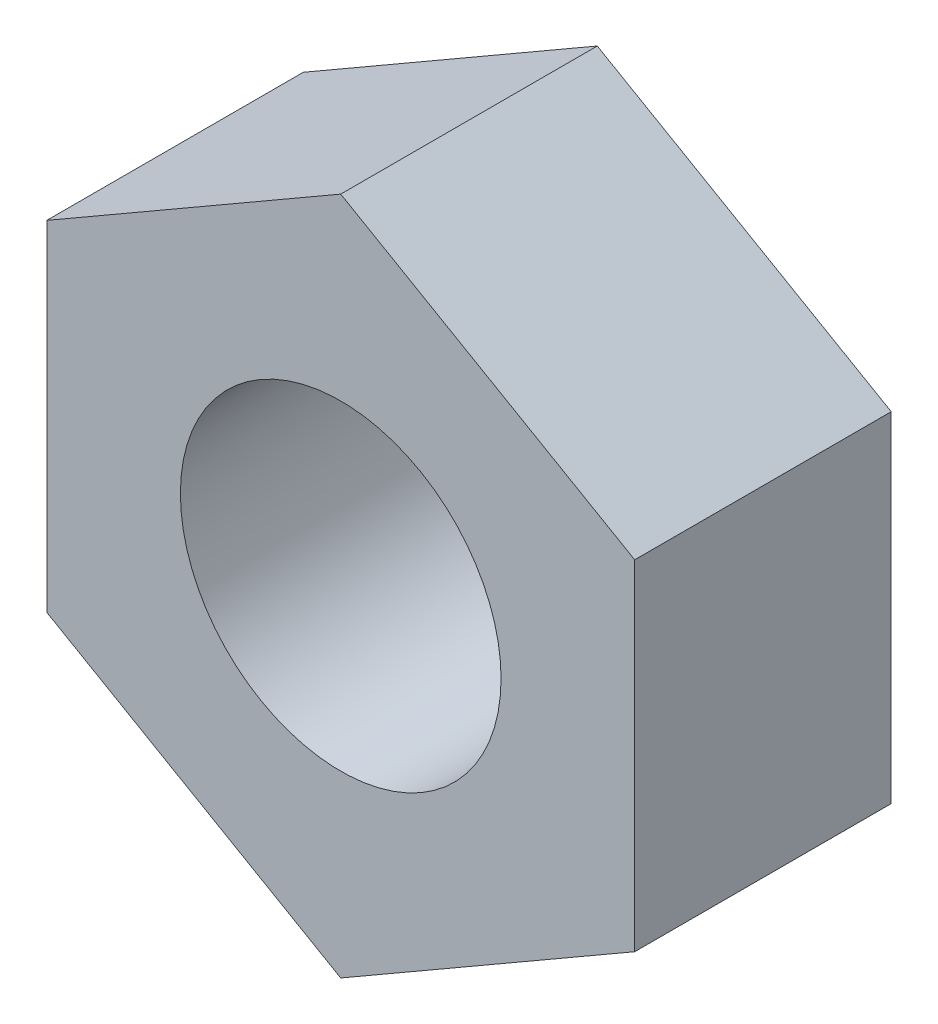
SolidWorks part; units mm, degrees
ref_plane "前视基准面" through (0, 0, 0) normal (0, 0, 1) x (1, 0, 0)
ref_plane "上视基准面" through (0, 0, 0) normal (0, 1, 0) x (1, 0, 0)
ref_plane "右视基准面" through (0, 0, 0) normal (1, 0, 0) x (0, 0, -1)
sketch "草图1" plane through (0, 0, 0) normal (0, 0, 1) x (1, 0, 0)
  line L1 (0, -3.1754) -> (2.75, -1.5877)
  line L2 (2.75, -1.5877) -> (2.75, 1.5877)
  line L3 (2.75, 1.5877) -> (0, 3.1754)
  line L4 (0, 3.1754) -> (-2.75, 1.5877)
  line L5 (-2.75, 1.5877) -> (-2.75, -1.5877)
  line L6 (-2.75, -1.5877) -> (0, -3.1754)
  circle A0 centre (0, 0) radius 2.75 construction
  circle A1 centre (0, 0) radius 1.5
extrude "凸台-拉伸1" add sketch "草图1" along normal blind 2.4 contours L6 L1 L2 L3 L4 L5 | A1
